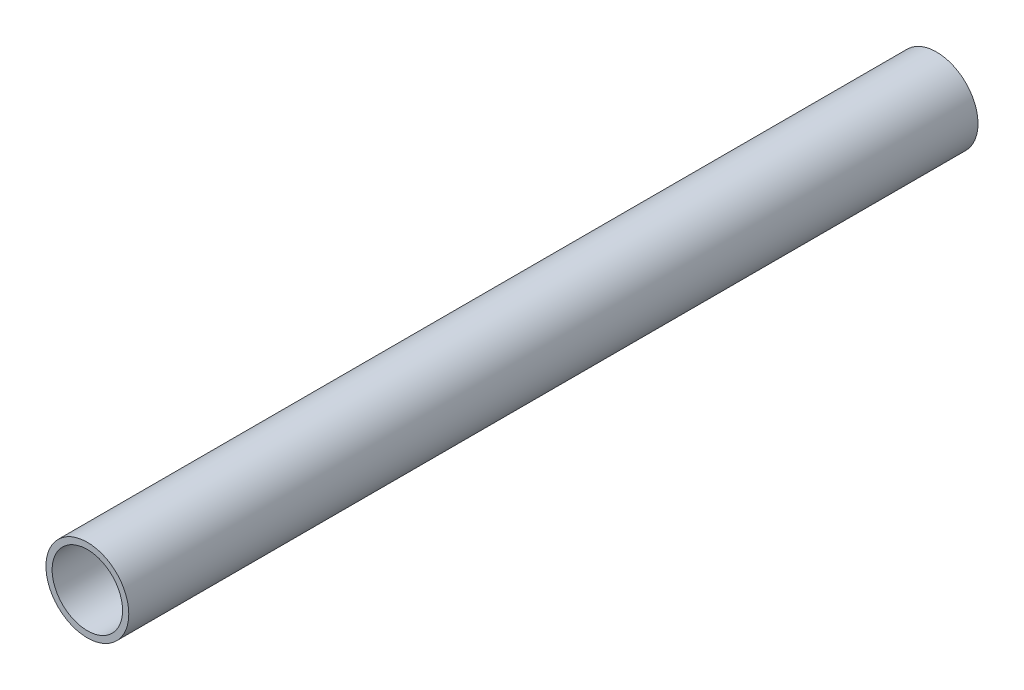
SolidWorks part; units mm, degrees
ref_plane "Front Plane" through (0, 0, 0) normal (0, 0, 1) x (1, 0, 0)
ref_plane "Top Plane" through (0, 0, 0) normal (0, 1, 0) x (1, 0, 0)
ref_plane "Right Plane" through (0, 0, 0) normal (1, 0, 0) x (0, 0, -1)
sketch "Sketch1" plane through (0, 0, 0) normal (0, 0, 1) x (1, 0, 0)
  circle A0 centre (0, 0) radius 20
  dimension "D1" = 40
extrude "Boss-Extrude1" add sketch "Sketch1" against normal blind 410
sketch "Sketch2" plane through (0, 0, 0) normal (0, 0, 1) x (1, 0, 0)
  circle A0 centre (0, 0) radius 17
  dimension "D1" = 34
extrude "Cut-Extrude1" cut sketch "Sketch2" against normal through all contours A0
